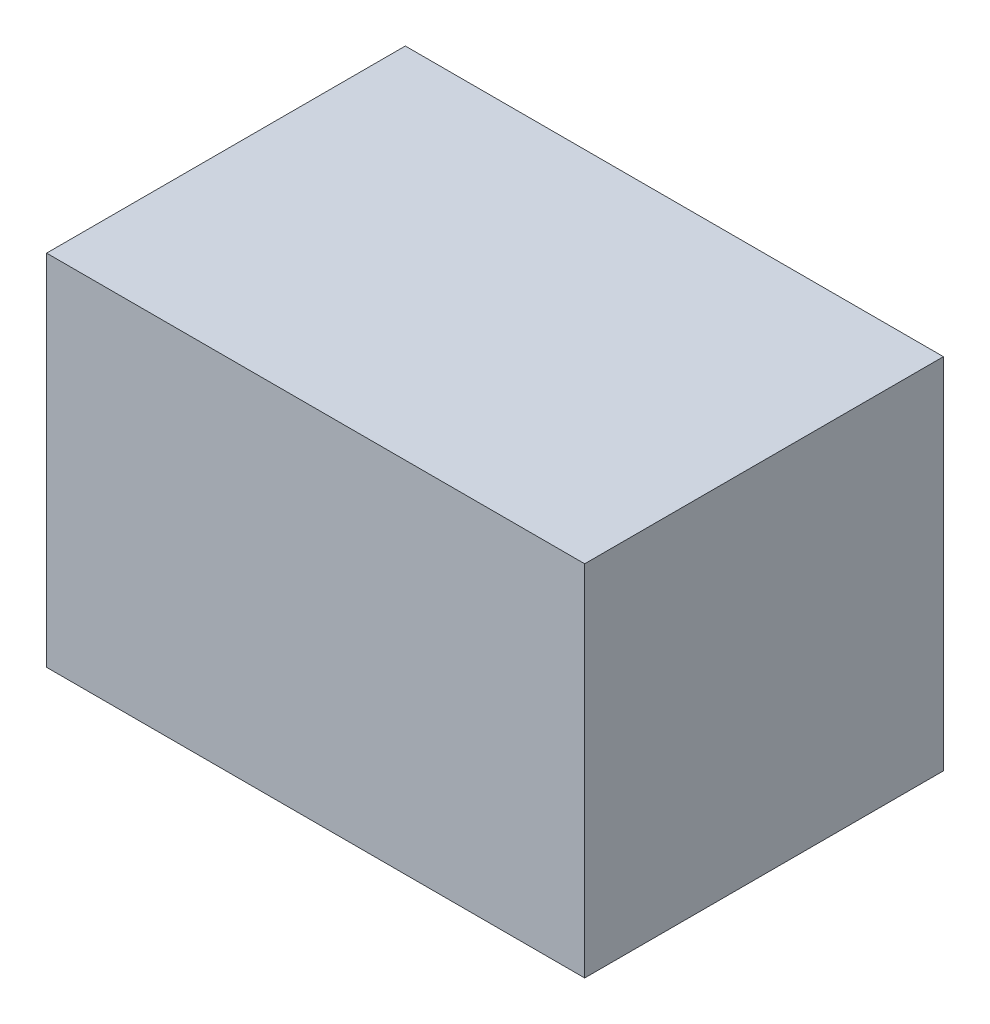
SolidWorks part; units mm, degrees
ref_plane "前视基准面" through (0, 0, 0) normal (0, 0, 1) x (1, 0, 0)
ref_plane "上视基准面" through (0, 0, 0) normal (0, 1, 0) x (1, 0, 0)
ref_plane "右视基准面" through (0, 0, 0) normal (1, 0, 0) x (0, 0, -1)
other "Configuration Table"
sketch "草图1" plane through (0, 0, 0) normal (0, 0, 1) x (1, 0, 0)
  line L1 (-30, -20) -> (30, -20)
  line L2 (-30, -20) -> (-30, 20)
  line L3 (-30, 20) -> (30, 20)
  line L4 (30, -20) -> (30, 20)
  line L5 (-30, -20) -> (30, 20) construction
  line L6 (-30, 20) -> (30, -20) construction
  point P0 (0, 0)
extrude "凸台-拉伸1" add sketch "草图1" along normal blind 40
